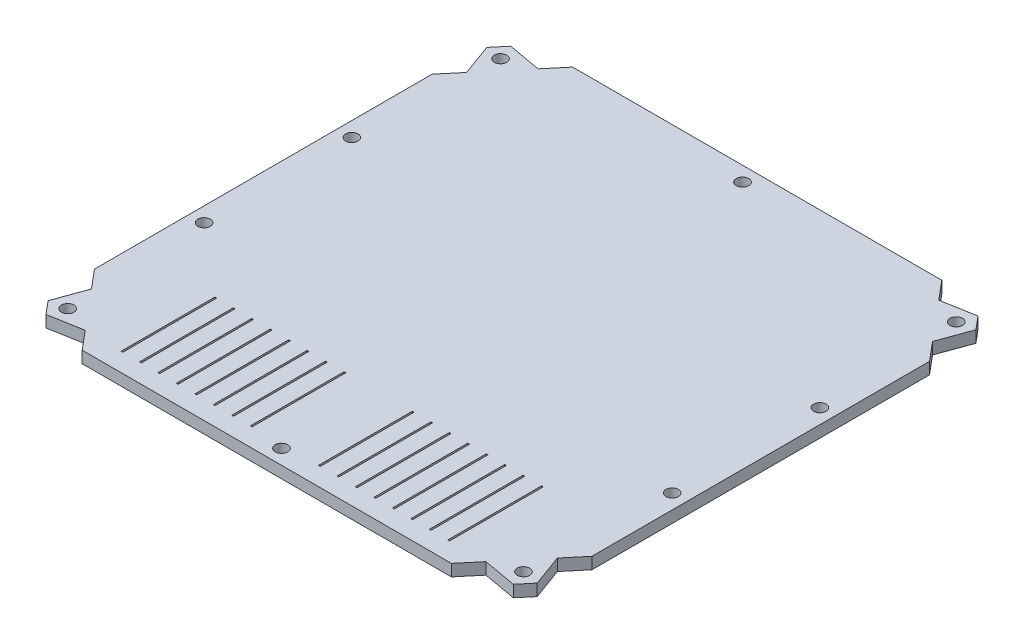
SolidWorks part; units mm, degrees
material "6061-T6 (SS)"
ref_plane "Front Plane" through (0, 0, 0) normal (0, 0, 1) x (1, 0, 0)
ref_plane "Top Plane" through (0, 0, 0) normal (0, 1, 0) x (1, 0, 0)
ref_plane "Right Plane" through (0, 0, 0) normal (1, 0, 0) x (0, 0, -1)
ref_plane "Plane1" through (0, 0, 72) normal (0, 0, 1) x (1, 0, 0)
sketch "Sketch1" plane through (0, 0, 0) normal (0, 1, 0) x (1, 0, 0)
  line L1 (-134.7, -132.8) -> (134.7, -132.8)
  line L2 (-134.7, -132.8) -> (-134.7, 132.8)
  line L3 (-134.7, 132.8) -> (134.7, 132.8)
  line L4 (134.7, -132.8) -> (134.7, 132.8)
  line L5 (-134.7, -132.8) -> (134.7, 132.8) construction
  line L6 (-134.7, 132.8) -> (134.7, -132.8) construction
  line L10 (-87, 122.8) -> (-95.3274, 122.8) construction
  line L11 (-124.7, 87.7951) -> (-124.7, 49.5) construction
  point P0 (0, 0)
  dimension "D1" = 10
  dimension "D2" = 10
extrude "Boss-Extrude1" add sketch "Sketch1" along normal mid plane 6.35
sketch "Sketch16" plane through (0, 3.175, 0) normal (0, 1, 0) x (1, 0, 0)
  line L0 (-134.7, 132.8) -> (-134.7, 91.4348)
  line L1 (-134.7, 132.8) -> (-134.7, -132.8) construction
  line L2 (-134.7, 91.4348) -> (-99.9905, 132.8)
  line L3 (134.7, 132.8) -> (-134.7, 132.8) construction
  line L4 (-99.9905, 132.8) -> (-134.7, 132.8)
  line L5 (0, -45.485) -> (0, 45.485) construction
  line L6 (99.9905, 132.8) -> (134.7, 132.8)
  line L7 (134.7, 91.4348) -> (99.9905, 132.8)
  line L8 (134.7, 132.8) -> (134.7, 91.4348)
  line L9 (-45.485, 0) -> (45.485, 0) construction
  line L10 (134.7, -132.8) -> (134.7, -91.4348)
  line L11 (134.7, -91.4348) -> (99.9905, -132.8)
  line L12 (99.9905, -132.8) -> (134.7, -132.8)
  line L13 (-99.9905, -132.8) -> (-134.7, -132.8)
  line L14 (-134.7, -91.4348) -> (-99.9905, -132.8)
  line L15 (-134.7, -132.8) -> (-134.7, -91.4348)
  line L17 (-124.7, 87.7951) -> (-95.3274, 122.8) construction
  dimension "D2" = 10
extrude "Cut-Extrude3" cut sketch "Sketch16" against normal through all
sketch "Sketch7" plane through (0, -3.175, 0) normal (0, 1, 0) x (1, 0, 0)
  line L0 (99.9905, 132.8) -> (134.7, 91.4348) construction
  line L5 (99.9905, 132.8) -> (134.7, 91.4348) construction
  line L20 (117.3452, 112.1174) -> (129.5062, 122.3217) construction
  line L22 (126.5605, 125.8322) -> (132.4519, 118.8111)
  line L23 (132.4519, 118.8111) -> (126.1824, 101.5857)
  line L24 (126.5605, 125.8322) -> (108.5081, 122.6491)
  line L25 (123.4257, 117.2195) -> (130.8845, 114.5048) construction
  line L26 (123.4257, 117.2195) -> (129.5062, 122.3217) construction
  line L27 (108.5081, 122.6491) -> (126.1824, 101.5857)
  point P6 (129.5062, 122.3217)
  point P10 (123.4257, 117.2195)
  point P14 (123.4257, 117.2195)
  dimension "D2" = 15.875
  dimension "D1" = 30
extrude "Boss-Extrude3" add sketch "Sketch7" along normal up to surface (6.35 mm away) up to face at (0, 3.175, 0)
hole_wizard "1/4 Clearance Hole1" positions "Sketch8" profile "Sketch9" hole size "1/4" standard "ANSI Inch" end condition through all
sketch "Sketch8" plane through (0, -3.175, 0) normal (0, 1, 0) x (1, 0, 0)
  line L0 (123.416, 117.2114) -> (129.5062, 122.3217) construction
  line L1 (132.4519, 118.8111) -> (126.5605, 125.8322) construction
  line L3 (126.7498, 40) -> (134.7, 40) construction
  line L4 (0, 132.8) -> (0, 124.8498) construction
  line L5 (99.9905, 132.8) -> (-99.9905, 132.8) construction
  line L7 (0, 0) -> (134.7, 0) construction
  line L8 (134.7, -91.4348) -> (134.7, 91.4348) construction
  point P25 (123.416, 117.2114)
  point P43 (126.7498, 40)
  point P55 (0, 124.8498)
  dimension "D1" = 7.9502
  dimension "D2" = 7.9502
  dimension "D3" = 7.9502
  dimension "D4" = 40
sketch "Sketch9" plane through (123.416, -3.175, -117.2114) normal (1, 0, 0) x (0, 0, -1)
  line L0 (0, 0) -> (0, 6.35)
  line L1 (0, 6.35) -> (3.3782, 6.35)
  line L2 (3.3782, 6.35) -> (3.3782, 0)
  line L5 (3.3782, 0) -> (0, 0)
  line L11 (0, -6.35) -> (0, 107.95) construction
  dimension "Thru Hole Dia." = 6.7564
  dimension "Thru Hole Depth" = 6.35
mirror "Mirror1" about plane through (0, 0, 0) normal (0, 0, 1) of "Boss-Extrude3", "1/4 Clearance Hole1"
mirror "Mirror2" about plane through (0, 0, 0) normal (1, 0, 0) of "Mirror1", "Boss-Extrude3", "1/4 Clearance Hole1"
sketch "Sketch15" plane through (0, 3.175, 0) normal (0, 1, 0) x (1, 0, 0)
  line L1 (-88.971, -122.8) -> (-88.027, -122.8)
  line L2 (-88.971, -122.8) -> (-88.971, -72)
  line L3 (-88.971, -72) -> (-88.027, -72)
  line L4 (-88.027, -122.8) -> (-88.027, -72)
  line L5 (-23.1, -72) -> (23.1, -72) construction
  dimension "D1" = 0.944
  dimension "D2" = 88.027
  dimension "D3" = 122.8
extrude "Cut-Extrude2" cut sketch "Sketch15" against normal up to next
pattern_linear "LPattern1" count 8 spacing 10 along (1, 0, 0) of "Cut-Extrude2"
mirror "Mirror3" about plane through (0, 0, 0) normal (1, 0, 0) of "LPattern1", "Cut-Extrude2"
sketch "Sketch17" [suppressed] plane through (0, 3.175, 0) normal (0, 1, 0) x (1, 0, 0)
  line L1 (-50, 15) -> (50, 15)
  line L2 (-50, 15) -> (-50, -15)
  line L3 (-50, -15) -> (50, -15)
  line L4 (50, 15) -> (50, -15)
  line L5 (-50, 15) -> (50, -15) construction
  line L6 (-50, -15) -> (50, 15) construction
  point P0 (0, 0)
  dimension "D1" = 100
  dimension "D2" = 30
extrude "Cut-Extrude4" [suppressed] cut sketch "Sketch17" against normal through all
fillet "Fillet1" [suppressed] radius 5
hole_wizard "#10 Clearance Hole1" [suppressed] positions "Sketch18" profile "Sketch19" hole size "#10" standard "ANSI Inch"
sketch "Sketch18" plane through (0, 3.175, 0) normal (0, 1, 0) x (1, 0, 0)
  line L0 (0, 0) -> (0, 21.35) construction
  line L2 (-56.35, 21.35) -> (56.35, 21.35) construction
  line L4 (45, 15) -> (-45, 15) construction
  line L7 (50, -10) -> (50, 10) construction
  point P2 (0, 21.35)
  point P7 (56.35, 21.35)
  dimension "D1" = 6.35
  dimension "D2" = 6.35
sketch "Sketch19" plane through (56.35, 3.175, -21.35) normal (1, 0, 0) x (0, 0, 1)
  line L0 (0, 0) -> (0, 6.35)
  line L1 (0, 6.35) -> (2.5527, 6.35)
  line L2 (2.5527, 6.35) -> (2.5527, 0)
  line L5 (2.5527, 0) -> (0, 0)
  line L11 (0, -6.35) -> (0, 107.95) construction
  dimension "Thru Hole Dia." = 5.1054
  dimension "Thru Hole Depth" = 6.35
mirror "Mirror4" [suppressed] about plane through (0, 0, 0) normal (0, 0, 1)
mirror "Mirror5" [suppressed] about plane through (0, 0, 0) normal (1, 0, 0)
equation "\"D2@Sketch7\"=0.3125*2in"
equation "\"D1\"= 1.190625mm"
equation "\"gasket_thickness\"= 1 / 32in"
equation "\"D3@Sketch8\"=\"D1@Sketch8\""
